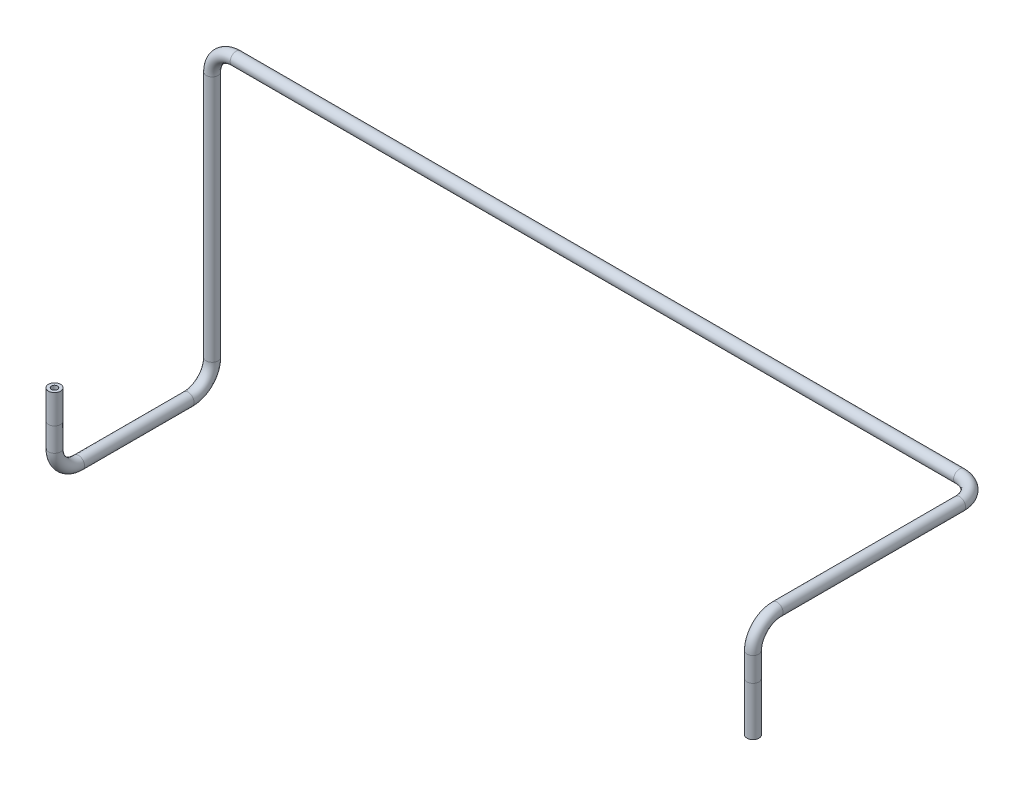
SolidWorks part; units mm, degrees
material "PVC 0.007 Plasticized"
ref_plane "Front Plane" through (0, 0, 0) normal (0, 0, 1) x (1, 0, 0)
ref_plane "Top Plane" through (0, 0, 0) normal (0, 1, 0) x (1, 0, 0)
ref_plane "Right Plane" through (0, 0, 0) normal (1, 0, 0) x (0, 0, -1)
sketch3d "3DSketch1"
  line L0 (-197.9397, -11.615, 57.1149) -> (-197.9397, -3.995, 57.1149)
  line L1 (-197.9397, -11.615, 57.1149) -> (-197.9397, -17.8782, 57.1149)
  line L2 (-197.9397, -24.2282, 50.7649) -> (-197.9397, -24.2282, 21.845)
  line L3 (-197.9397, -17.8782, 15.495) -> (-197.9397, 47.3857, 15.495)
  line L4 (5.7803, 41.021, 76.4052) -> (5.7803, 28.1548, 76.4052)
  line L5 (5.7803, 41.021, 76.4052) -> (5.7803, 47.3857, 76.4052)
  line L6 (5.7803, 53.7357, 70.0552) -> (5.7803, 53.7357, 21.845)
  line L7 (-191.5897, 53.7357, 15.495) -> (-0.5697, 53.7357, 15.495)
  circle A0 centre (-197.9397, -11.615, 57.1149) radius 0.635 construction
  circle A1 centre (-197.9397, -3.995, 57.1149) radius 0.635 construction
  circle A2 centre (5.7803, 41.021, 76.4052) radius 1.1906 construction
  arc A3 (-197.9397, -17.8782, 57.1149) -> (-197.9397, -24.2282, 50.7649) centre (-197.9397, -17.8782, 50.7649) ccw
  arc A4 (-197.9397, -24.2282, 21.845) -> (-197.9397, -17.8782, 15.495) centre (-197.9397, -17.8782, 21.845) ccw
  arc A5 (-197.9397, 47.3857, 15.495) -> (-191.5897, 53.7357, 15.495) centre (-191.5897, 47.3857, 15.495) ccw
  arc A6 (5.7803, 53.7357, 21.845) -> (-0.5697, 53.7357, 15.495) centre (-0.5697, 53.7357, 21.845) ccw
  arc A7 (5.7803, 47.3857, 76.4052) -> (5.7803, 53.7357, 70.0552) centre (5.7803, 47.3857, 70.0552) ccw
  point P0 (-197.9397, -11.615, 57.1149)
  point P4 (-197.9397, -12.25, 57.1149)
  point P8 (-197.9397, -4.63, 57.1149)
  point P16 (5.7803, 42.2116, 76.4052)
  point P21 (-197.9397, -24.2282, 57.1149)
  point P22 (-191.5897, -17.8782, 50.7649)
  point P25 (-197.9397, -24.2282, 15.495)
  point P26 (-191.5897, -17.8782, 21.845)
  point P29 (-197.9397, 53.7357, 15.495)
  point P30 (-191.5897, 47.3857, 9.145)
  point P33 (5.7803, 53.7357, 15.495)
  point P34 (-0.5697, 60.0857, 21.845)
  point P37 (5.7803, 53.7357, 76.4052)
  point P38 (-0.5697, 47.3857, 70.0552)
  dimension "D1" = 6.35
  dimension "D2" = 6.35
ref_plane "Plane1" through (-197.9397, -3.995, 57.1149) normal (0, 1, 0) x (1, 0, 0)
sketch "Sketch1" plane through (-197.9397, -3.995, 57.1149) normal (0, 1, 0) x (1, 0, 0)
  circle A0 centre (0, 0) radius 1.5875
  circle A1 centre (0, 0) radius 0.8001
  dimension "D1" = 3.175
  dimension "D2" = 1.6002
sweep "Sweep1" add profiles "Sketch1" path "3DSketch1"
